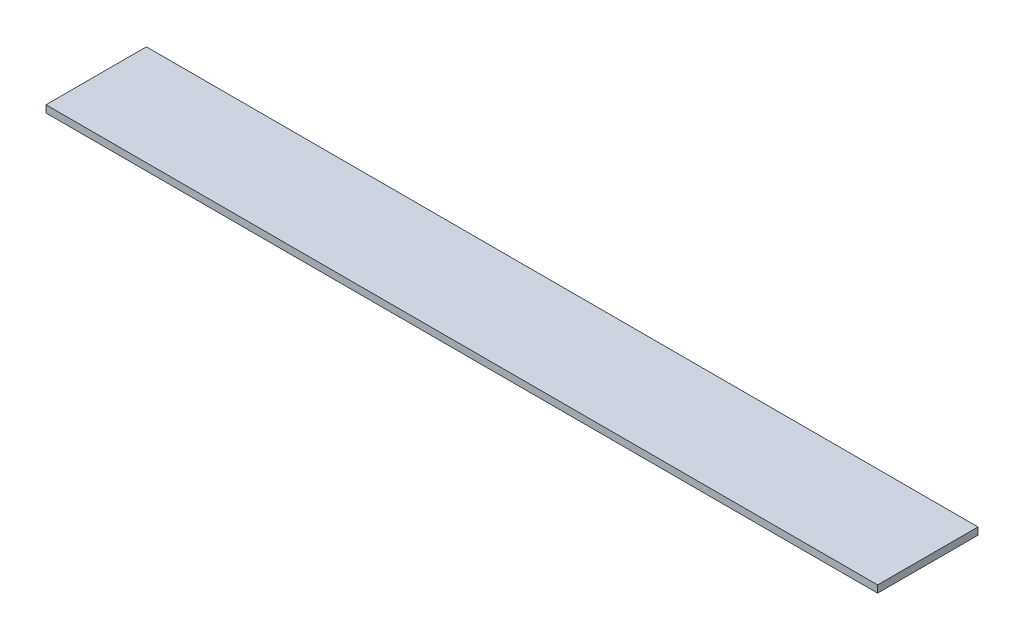
SolidWorks part; units mm, degrees
ref_plane "Front Plane" through (0, 0, 0) normal (0, 0, 1) x (1, 0, 0)
ref_plane "Top Plane" through (0, 0, 0) normal (0, 1, 0) x (1, 0, 0)
ref_plane "Right Plane" through (0, 0, 0) normal (1, 0, 0) x (0, 0, -1)
sketch "Sketch1" plane through (0, 0, 0) normal (0, 1, 0) x (1, 0, 0)
  line L1 (-290, 35) -> (290, 35)
  line L2 (-290, 35) -> (-290, -35)
  line L3 (-290, -35) -> (290, -35)
  line L4 (290, 35) -> (290, -35)
  point P4 (0, -35)
  point P6 (-290, 0)
  dimension "D1" = 580
  dimension "D2" = 70
extrude "Boss-Extrude1" add sketch "Sketch1" along normal blind 5
